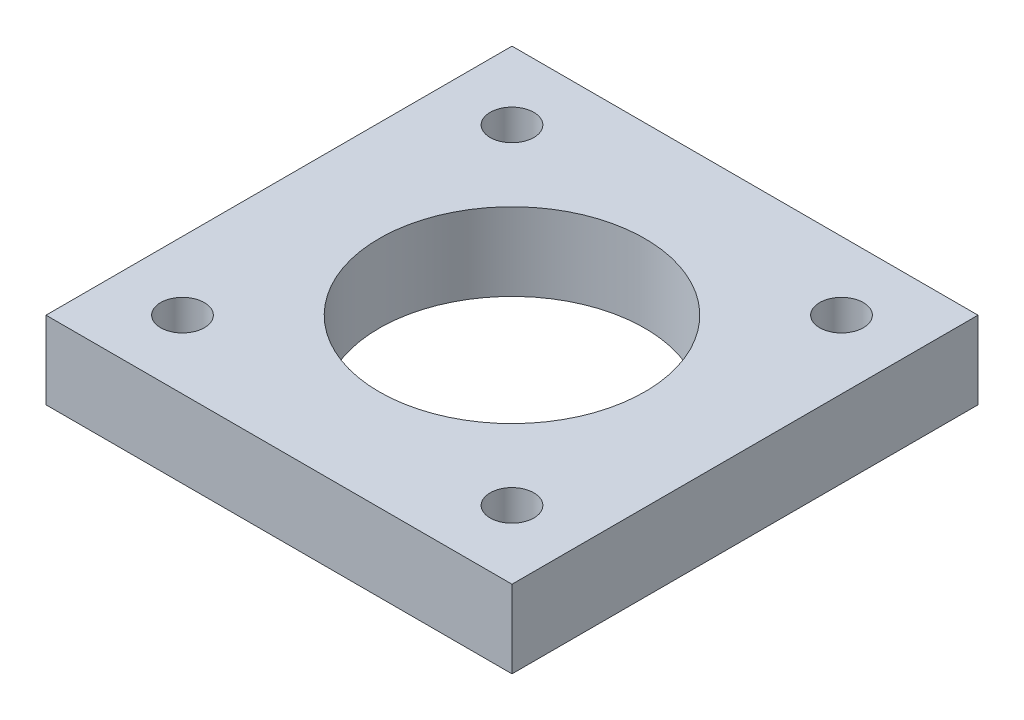
SolidWorks part; units mm, degrees
ref_plane "Front Plane" through (0, 0, 0) normal (0, 0, 1) x (1, 0, 0)
ref_plane "Top Plane" through (0, 0, 0) normal (0, 1, 0) x (1, 0, 0)
ref_plane "Right Plane" through (0, 0, 0) normal (1, 0, 0) x (0, 0, -1)
sketch "Sketch1" plane through (0, 0, 0) normal (0, 1, 0) x (1, 0, 0)
  line L0 (0, 0) -> (38.1, 38.1) construction
  line L1 (0, 0) -> (38.1, 0)
  line L2 (0, 0) -> (0, 38.1)
  line L3 (0, 38.1) -> (38.1, 38.1)
  line L4 (38.1, 0) -> (38.1, 38.1)
  line L5 (0, 38.1) -> (38.1, 0) construction
  circle A0 centre (19.05, 19.05) radius 10.8585
  circle A1 centre (19.05, 19.05) radius 19.05 construction
  circle A2 centre (5.5796, 32.5204) radius 1.7859
  circle A3 centre (32.5204, 32.5204) radius 1.7859
  circle A4 centre (32.5204, 5.5796) radius 1.7859
  circle A5 centre (5.5796, 5.5796) radius 1.7859
  point P8 (5.5796, 32.5204)
  point P9 (32.5204, 32.5204)
  point P10 (32.5204, 5.5796)
  point P11 (5.5796, 5.5796)
  dimension "D3" = 21.717
  dimension "D4" = 3.5719
  dimension "D5" = 3.5719
  dimension "D6" = 3.5719
  dimension "D7" = 3.5719
  dimension "D1" = 38.1
  dimension "D2" = 38.1
extrude "Extrude1" add sketch "Sketch1" along normal blind 6.35
